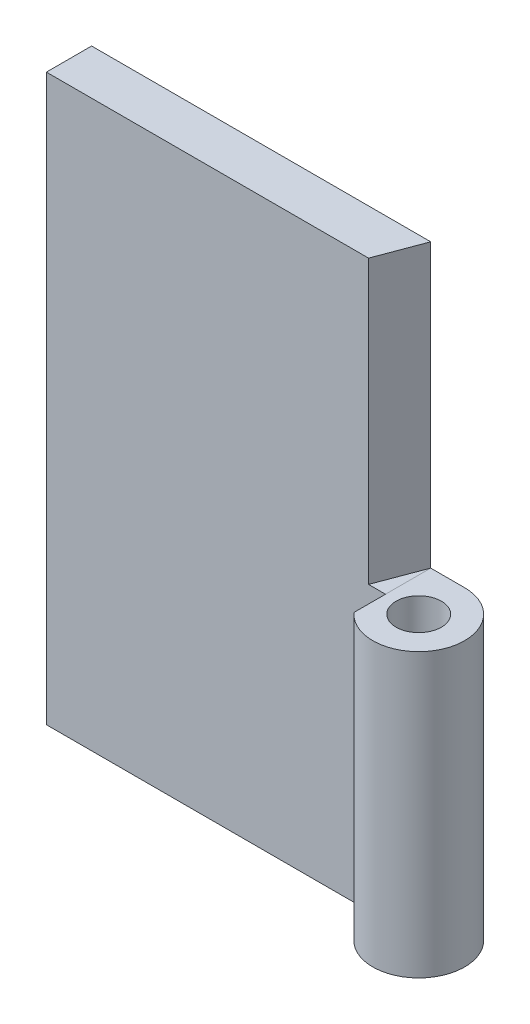
SolidWorks part; units mm, degrees
ref_plane "Front Plane" through (0, 0, 0) normal (0, 0, 1) x (1, 0, 0)
ref_plane "Top Plane" through (0, 0, 0) normal (0, 1, 0) x (1, 0, 0)
ref_plane "Right Plane" through (0, 0, 0) normal (1, 0, 0) x (0, 0, -1)
sketch "Sketch1" plane through (0, 0, 0) normal (0, 0, 1) x (1, 0, 0)
  line L1 (0, 0) -> (15, 0)
  line L2 (0, 0) -> (0, -25)
  line L3 (0, -25) -> (15, -25)
  line L4 (15, 0) -> (15, -25)
  dimension "D1" = 15
  dimension "D2" = 25
extrude "Boss-Extrude1" add sketch "Sketch1" along normal blind 2
sketch "Sketch2" plane through (0, 0, 0) normal (0, 1, 0) x (1, 0, 0)
  line L0 (15, 0) -> (16.5, 0)
  line L2 (15, 0) -> (15, -3.4)
  arc A0 (15, -3.4) -> (16.5, 0) centre (16.5, -2.0309) ccw
  point P1 (15, -2)
  dimension "D1" = 3.4
  dimension "D2" = 1.5
sketch "Sketch4" plane through (0, -25, 0) normal (0, -1, 0) x (1, 0, 0)
  line L4 (15, 0) -> (16.5, 0)
  line L5 (15, 3.4) -> (15, 0)
  line L6 (15, 0) -> (16.5, 0)
  line L7 (15, 3.4) -> (15, 0)
  arc A2 (16.5, 0) -> (15, 3.4) centre (16.5, 2.0309) ccw
  arc A3 (16.5, 0) -> (15, 3.4) centre (16.5, 2.0309) ccw
  point P2 (0, 0)
  dimension "D1" = 0
extrude "Boss-Extrude3" add sketch "Sketch4" against normal blind 12.5 separate body
sketch "Sketch5" plane through (0, -25, 0) normal (0, -1, 0) x (1, 0, 0)
  circle A0 centre (16.5, 2.0309) radius 1
  arc A1 (16.5, 0) -> (15, 3.4) centre (16.5, 2.0309) ccw construction
  point P2 (0, 0)
  dimension "D1" = 2
extrude "Cut-Extrude2" cut sketch "Sketch5" against normal through all
sketch "Sketch7" plane through (0, 0, 0) normal (0, 1, 0) x (1, 0, 0)
  line L1 (15, -2) -> (0, -2) construction
  line L3 (15, -2) -> (15, 0) construction
  line L4 (15, 0) -> (14.25, -2)
  line L5 (14.25, -2) -> (15, -2)
  line L6 (15, -2) -> (15, 0)
  dimension "D1" = 0.75
extrude "Cut-Extrude4" cut sketch "Sketch7" against normal up to surface (12.5 mm away) up to face at (16.5, -12.5, 1.0309)
